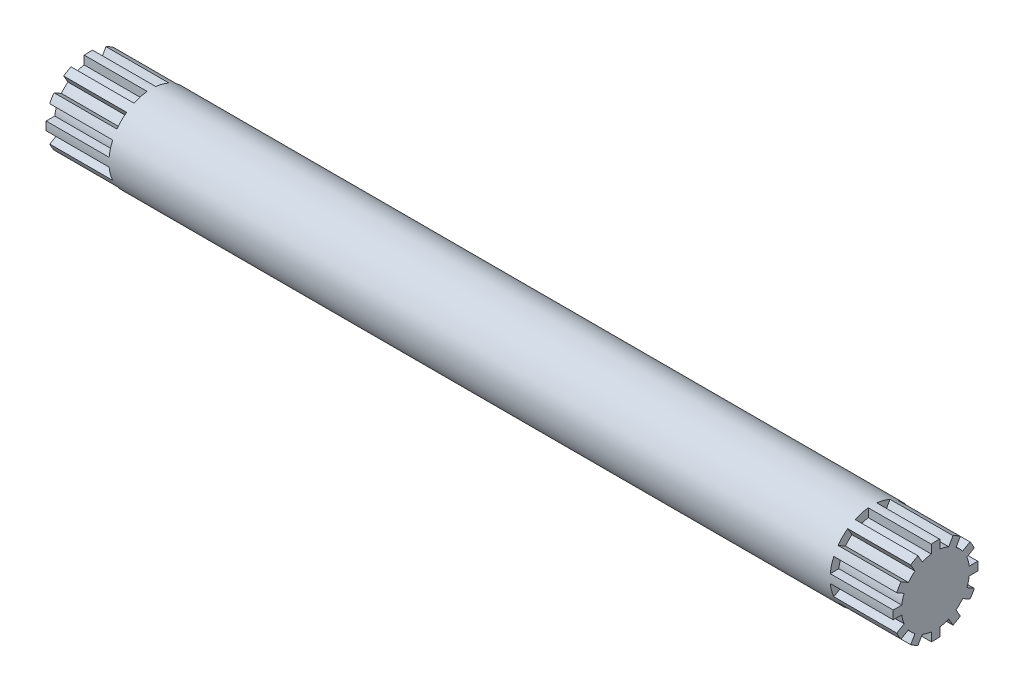
SolidWorks part; units mm, degrees
ref_plane "Front Plane" through (0, 0, 0) normal (0, 0, 1) x (1, 0, 0)
ref_plane "Top Plane" through (0, 0, 0) normal (0, 1, 0) x (1, 0, 0)
ref_plane "Right Plane" through (0, 0, 0) normal (1, 0, 0) x (0, 0, -1)
sketch "Sketch1" plane through (0, 0, 0) normal (1, 0, 0) x (0, 0, -1)
  circle A0 centre (0, 0) radius 2.5
  dimension "D1" = 5
extrude "Boss-Extrude1" add sketch "Sketch1" along normal blind 49.8
sketch "Sketch3" plane through (0, 0, 0) normal (-1, 0, 0) x (0, 0, 1)
  line L0 (-4.0331, 0) -> (4.3806, 0) construction
  line L1 (-2.5377, -0.25) -> (-1.9843, -0.25)
  line L2 (-2.5377, 0.25) -> (-1.9843, 0.25)
  line L3 (-2.0727, 1.4854) -> (-1.5935, 1.2087)
  line L4 (-2.3227, 1.0524) -> (-1.8435, 0.7757)
  line L5 (-1.0524, 2.3227) -> (-0.7757, 1.8435)
  line L6 (-1.4854, 2.0727) -> (-1.2087, 1.5935)
  line L7 (0.25, 2.5377) -> (0.25, 1.9843)
  line L8 (-0.25, 2.5377) -> (-0.25, 1.9843)
  line L9 (1.4854, 2.0727) -> (1.2087, 1.5935)
  line L10 (1.0524, 2.3227) -> (0.7757, 1.8435)
  line L11 (2.3227, 1.0524) -> (1.8435, 0.7757)
  line L12 (2.0727, 1.4854) -> (1.5935, 1.2087)
  line L13 (2.5377, -0.25) -> (1.9843, -0.25)
  line L14 (2.5377, 0.25) -> (1.9843, 0.25)
  line L15 (2.0727, -1.4854) -> (1.5935, -1.2087)
  line L16 (2.3227, -1.0524) -> (1.8435, -0.7757)
  line L17 (1.0524, -2.3227) -> (0.7757, -1.8435)
  line L18 (1.4854, -2.0727) -> (1.2087, -1.5935)
  line L19 (-0.25, -2.5377) -> (-0.25, -1.9843)
  line L20 (0.25, -2.5377) -> (0.25, -1.9843)
  line L21 (-1.4854, -2.0727) -> (-1.2087, -1.5935)
  line L22 (-1.0524, -2.3227) -> (-0.7757, -1.8435)
  line L23 (-2.3227, -1.0524) -> (-1.8435, -0.7757)
  line L24 (-2.0727, -1.4854) -> (-1.5935, -1.2087)
  arc A0 (-2.5377, -0.25) -> (-2.3227, -1.0524) centre (0, 0) ccw
  arc A1 (-1.9843, -0.25) -> (-1.8435, -0.7757) centre (0, 0) ccw
  arc A2 (-1.8435, 0.7757) -> (-1.9843, 0.25) centre (0, 0) ccw
  arc A3 (-2.3227, 1.0524) -> (-2.5377, 0.25) centre (0, 0) ccw
  arc A4 (-1.2087, 1.5935) -> (-1.5935, 1.2087) centre (0, 0) ccw
  arc A5 (-1.4854, 2.0727) -> (-2.0727, 1.4854) centre (0, 0) ccw
  arc A6 (-0.25, 2.5377) -> (-1.0524, 2.3227) centre (0, 0) ccw
  arc A7 (-0.25, 1.9843) -> (-0.7757, 1.8435) centre (0, 0) ccw
  arc A8 (1.0524, 2.3227) -> (0.25, 2.5377) centre (0, 0) ccw
  arc A9 (0.7757, 1.8435) -> (0.25, 1.9843) centre (0, 0) ccw
  arc A10 (2.0727, 1.4854) -> (1.4854, 2.0727) centre (0, 0) ccw
  arc A11 (1.5935, 1.2087) -> (1.2087, 1.5935) centre (0, 0) ccw
  arc A12 (1.9843, 0.25) -> (1.8435, 0.7757) centre (0, 0) ccw
  arc A13 (2.5377, 0.25) -> (2.3227, 1.0524) centre (0, 0) ccw
  arc A14 (1.8435, -0.7757) -> (1.9843, -0.25) centre (0, 0) ccw
  arc A15 (2.3227, -1.0524) -> (2.5377, -0.25) centre (0, 0) ccw
  arc A16 (1.2087, -1.5935) -> (1.5935, -1.2087) centre (0, 0) ccw
  arc A17 (1.4854, -2.0727) -> (2.0727, -1.4854) centre (0, 0) ccw
  arc A18 (0.25, -1.9843) -> (0.7757, -1.8435) centre (0, 0) ccw
  arc A19 (0.25, -2.5377) -> (1.0524, -2.3227) centre (0, 0) ccw
  arc A20 (-0.7757, -1.8435) -> (-0.25, -1.9843) centre (0, 0) ccw
  arc A21 (-1.0524, -2.3227) -> (-0.25, -2.5377) centre (0, 0) ccw
  arc A22 (-1.5935, -1.2087) -> (-1.2087, -1.5935) centre (0, 0) ccw
  arc A23 (-2.0727, -1.4854) -> (-1.4854, -2.0727) centre (0, 0) ccw
  point P56 (0, 0)
  dimension "D1" = 5.1
  dimension "D2" = 4
  dimension "D3" = 0.25
  dimension "D4" = 0.25
  dimension "D5" = 12
extrude "Cut-Extrude2" cut sketch "Sketch3" against normal blind 3.7
ref_plane "Plane1" through (24.9, 0, 0) normal (1, 0, 0) x (0, 0, -1)
mirror "Mirror1" about plane through (24.9, 0, 0) normal (1, 0, 0) of "Cut-Extrude2"
